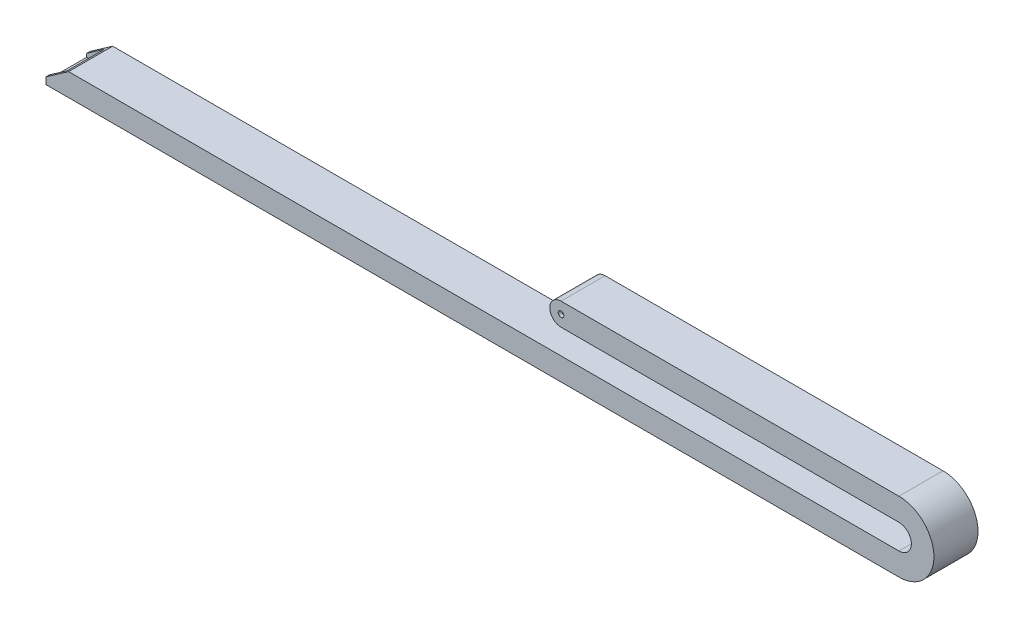
SolidWorks part; units mm, degrees
material "PA Type 6"
ref_plane "Front Plane" through (0, 0, 0) normal (0, 0, 1) x (1, 0, 0)
ref_plane "Top Plane" through (0, 0, 0) normal (0, 1, 0) x (1, 0, 0)
ref_plane "Right Plane" through (0, 0, 0) normal (1, 0, 0) x (0, 0, -1)
sketch "Sketch1" plane through (0, 0, 0) normal (0, 0, 1) x (1, 0, 0)
  line L6 (309.0621, 40) -> (-425.9023, 40)
  line L7 (10, 62) -> (309.0621, 62)
  line L8 (309.0621, 82) -> (10, 82)
  line L9 (-445.8964, 20) -> (309.0621, 20)
  line L10 (-445.8964, 26) -> (-445.8964, 20)
  line L11 (-425.9023, 40) -> (-445.8964, 26)
  line L12 (309.0621, 40) -> (-425.9023, 40)
  line L13 (10, 62) -> (309.0621, 62)
  line L14 (309.0621, 82) -> (10, 82)
  line L15 (-445.8964, 20) -> (309.0621, 20)
  line L16 (-445.8964, 26) -> (-445.8964, 20)
  line L17 (-425.9023, 40) -> (-445.8964, 26)
  arc A3 (309.0621, 40) -> (309.0621, 62) centre (309.0621, 51) ccw
  arc A4 (10, 82) -> (10, 62) centre (10, 72) ccw
  arc A5 (309.0621, 20) -> (309.0621, 82) centre (309.0621, 51) ccw
  arc A6 (309.0621, 40) -> (309.0621, 62) centre (309.0621, 51) ccw
  arc A7 (10, 82) -> (10, 62) centre (10, 72) ccw
  arc A8 (309.0621, 20) -> (309.0621, 82) centre (309.0621, 51) ccw
  dimension "D1" = 0
extrude "Boss-Extrude1" add sketch "Sketch1" along normal blind 39
shell "Shell1" thickness 3
sketch "Sketch2" plane through (-445.8964, 0, 0) normal (-1, 0, 0) x (0, 0, 1)
  line L1 (3, 79) -> (36, 79)
  line L2 (3, 79) -> (3, 65)
  line L3 (3, 65) -> (36, 65)
  line L4 (36, 79) -> (36, 65)
  line L5 (3, 37) -> (36, 37)
  line L6 (3, 37) -> (3, 23)
  line L7 (3, 23) -> (36, 23)
  line L8 (36, 37) -> (36, 23)
extrude "Cut-Extrude1" cut sketch "Sketch2" against normal up to vertex (455.8964 mm away) up to point (10, 82, 39)
sketch "Sketch3" plane through (0, 0, 39) normal (0, 0, 1) x (1, 0, 0)
  circle A0 centre (10, 72) radius 2.5
  dimension "D1" = 5
extrude "Cut-Extrude2" cut sketch "Sketch3" against normal through all
